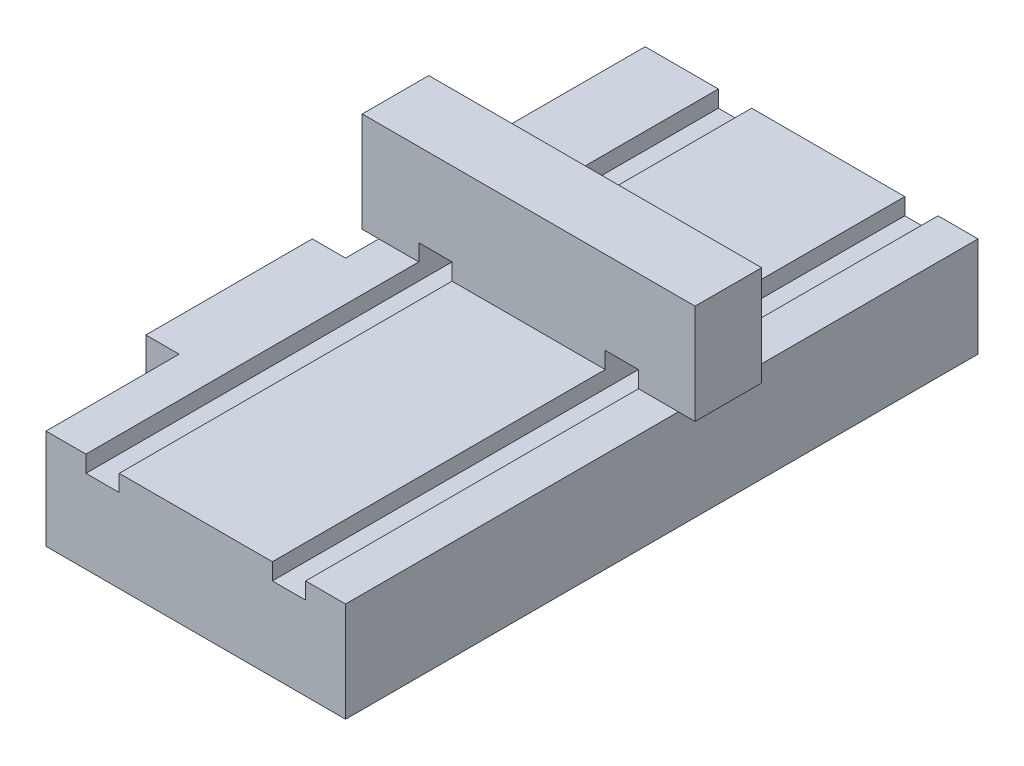
SolidWorks part; units mm, degrees
ref_plane "Front Plane" through (0, 0, 0) normal (0, 0, 1) x (1, 0, 0)
ref_plane "Top Plane" through (0, 0, 0) normal (0, 1, 0) x (1, 0, 0)
ref_plane "Right Plane" through (0, 0, 0) normal (1, 0, 0) x (0, 0, -1)
sketch "Sketch1" plane through (0, 0, 0) normal (0, 1, 0) x (1, 0, 0)
  line L12 (10, 0) -> (10, 40)
  line L13 (10, 0) -> (100, 0)
  line L14 (0, 40) -> (0, 90)
  line L15 (0, 190) -> (100, 190)
  line L16 (100, 0) -> (100, 190)
  line L17 (10, 40) -> (0, 40)
  line L18 (0, 90) -> (10, 90)
  line L19 (10, 90) -> (10, 140)
  line L20 (10, 140) -> (0, 140)
  line L21 (0, 190) -> (0, 140)
extrude "Boss-Extrude2" add sketch "Sketch1" along normal blind 30 contours L21 L20 L19 L18 L14 L17 L12 L13 L16 L15
sketch "Sketch2" plane through (0, 30, 0) normal (0, 1, 0) x (1, 0, 0)
  line L0 (22, 0) -> (22, 190)
  line L1 (10, 0) -> (100, 0) construction
  line L2 (0, 190) -> (100, 190) construction
  line L3 (78, 190) -> (78, 0)
  line L4 (32, 190) -> (32, 0)
  line L5 (88, 190) -> (88, 0)
  line L7 (22, 190) -> (32, 190)
  line L8 (22, 190) -> (22, 0)
  line L9 (22, 0) -> (32, 0)
  line L10 (32, 190) -> (32, 0)
  line L11 (78, 190) -> (88, 190)
  line L12 (78, 190) -> (78, 0)
  line L13 (78, 0) -> (88, 0)
  line L14 (88, 190) -> (88, 0)
  line M5 (100, 190) -> (0, 190)
  line M13 (10, 0) -> (100, 0)
extrude "Cut-Extrude8" cut sketch "Sketch2" against normal blind 5 contours L4 L0 M5 M13
sketch "Sketch7" plane through (0, 30, 0) normal (0, 1, 0) x (1, 0, 0)
  line L0 (78, 190) -> (78, 0)
  line L1 (32, 190) -> (100, 190) construction
  line L2 (32, 0) -> (100, 0) construction
  line L3 (88, 190) -> (88, 0)
  line L5 (78, 190) -> (88, 190)
  line L6 (78, 190) -> (78, 0)
  line L7 (78, 0) -> (88, 0)
  line L8 (88, 190) -> (88, 0)
  line M7 (100, 190) -> (32, 190)
  line M9 (32, 0) -> (100, 0)
extrude "Cut-Extrude9" cut sketch "Sketch7" against normal blind 5 contours L3 L0 M7 M9
sketch "Sketch10" plane through (0, 30, 0) normal (0, 1, 0) x (1, 0, 0)
  line L0 (10, 100) -> (100, 100)
  line L1 (10, 90) -> (10, 140) construction
  line L2 (100, 0) -> (100, 190) construction
  line L3 (100, 100) -> (100, 120)
  line L4 (100, 120) -> (10, 120)
  line L5 (10, 120) -> (10, 100)
  point P6 (0, 0)
  point P9 (0, 0)
  point P10 (0, 0)
  point P11 (0, 0)
  point P12 (0, 0)
  point P13 (0, 0)
extrude "Boss-Extrude9" add sketch "Sketch10" along normal blind 30
sketch "Sketch11" plane through (0, 0, -100) normal (0, 0, 1) x (1, 0, 0)
  line L0 (22, 30) -> (22, 35)
  line L1 (22, 35) -> (32, 35)
  line L2 (32, 35) -> (32, 30)
  line L3 (22, 30) -> (32, 30) construction
  line L4 (78, 30) -> (78, 35)
  line L5 (78, 35) -> (88, 35)
  line L6 (88, 35) -> (88, 30)
sketch "Sketch16" plane through (0, 0, -120) normal (0, 0, -1) x (-1, 0, 0)
  line L1 (-88, 35) -> (-78, 35)
  line L2 (-88, 35) -> (-88, 30)
  line L3 (-88, 30) -> (-78, 30)
  line L4 (-78, 35) -> (-78, 30)
extrude "Cut-Extrude11" cut sketch "Sketch16" against normal blind 34
sketch "Sketch18" plane through (0, 0, -120) normal (0, 0, -1) x (-1, 0, 0)
  line L1 (-32, 35) -> (-22, 35)
  line L2 (-32, 35) -> (-32, 30)
  line L3 (-32, 30) -> (-22, 30)
  line L4 (-22, 35) -> (-22, 30)
extrude "Cut-Extrude12" cut sketch "Sketch18" against normal blind 36
sketch "Sketch20" plane through (10, 0, 0) normal (-1, 0, 0) x (0, 0, 1)
  line L0 (-120, 30) -> (-100, 30)
split "Split3" trim tools "Sketch20" bodies to split 118 resulting bodies 126 127
sketch "Sketch24" plane through (10, 0, 0) normal (-1, 0, 0) x (0, 0, 1)
  line L1 (-120, 60) -> (-100, 60)
  line L2 (-120, 60) -> (-120, 30)
  line L3 (-120, 30) -> (-100, 30)
  line L4 (-100, 60) -> (-100, 30)
extrude "Boss-Extrude10" add sketch "Sketch24" along normal blind 5
sketch "Sketch25" plane through (100, 0, 0) normal (1, 0, 0) x (0, 0, -1)
  line L1 (100, 60) -> (120, 60)
  line L2 (100, 60) -> (100, 30)
  line L3 (100, 30) -> (120, 30)
  line L4 (120, 60) -> (120, 30)
extrude "Boss-Extrude11" add sketch "Sketch25" along normal blind 5
